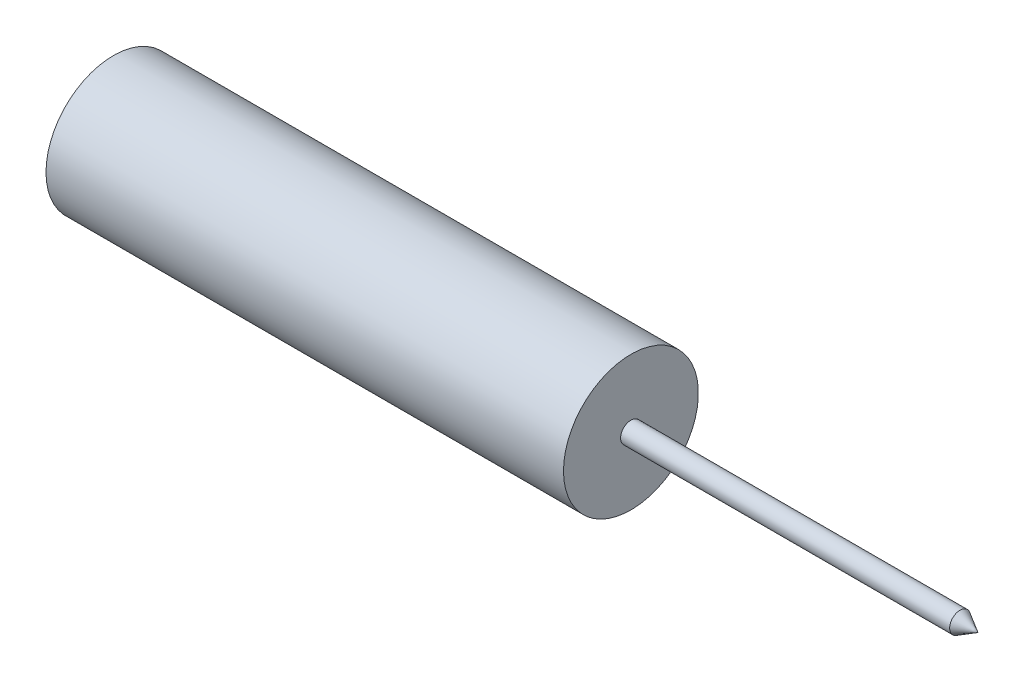
SolidWorks part; units mm, degrees
ref_plane "Front Plane" through (0, 0, 0) normal (0, 0, 1) x (1, 0, 0)
ref_plane "Top Plane" through (0, 0, 0) normal (0, 1, 0) x (1, 0, 0)
ref_plane "Right Plane" through (0, 0, 0) normal (1, 0, 0) x (0, 0, -1)
sketch "Sketch1" plane through (0, 0, 0) normal (0, 1, 0) x (1, 0, 0)
  line L0 (0, 0) -> (41.664, 0) construction
  line L1 (40.798, 0.5) -> (41.664, 0)
  line L2 (24.938, 3.25) -> (0, 3.25)
  line L3 (0, 3.25) -> (0, 0)
  line L4 (24.938, 3.25) -> (24.938, 0.5)
  line L5 (24.938, 0.5) -> (40.798, 0.5)
  line L6 (40.798, 0.5) -> (40.798, 0) construction
  line L7 (0, 0) -> (41.664, 0)
  dimension "D1" = 24.938
  dimension "D2" = 3.25
  dimension "D3" = 0.5
  dimension "D4" = 30
  dimension "D5" = 15.86
revolve "Revolve1" add sketch "Sketch1" angle 360 about L7
